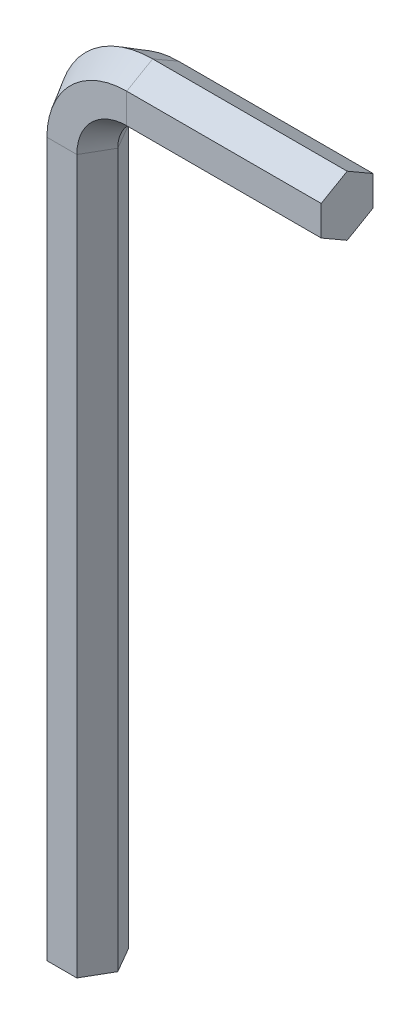
SolidWorks part; units mm, degrees
ref_plane "Front Plane" through (0, 0, 0) normal (0, 0, 1) x (1, 0, 0)
ref_plane "Top Plane" through (0, 0, 0) normal (0, 1, 0) x (1, 0, 0)
ref_plane "Right Plane" through (0, 0, 0) normal (1, 0, 0) x (0, 0, -1)
sketch "Sketch1" plane through (0, 0, 0) normal (0, 0, 1) x (1, 0, 0)
  line L0 (0, 0) -> (0, 110)
  line L1 (10, 120) -> (40, 120)
  arc A0 (0, 110) -> (10, 120) centre (10, 110) cw
  point P6 (0, 120)
  dimension "D3" = 10
  dimension "D1" = 120
  dimension "D2" = 40
sketch "Sketch2" plane through (0, 0, 0) normal (0, 1, 0) x (1, 0, 0)
  line L1 (4.6188, 0) -> (2.3094, 4)
  line L2 (2.3094, 4) -> (-2.3094, 4)
  line L3 (-2.3094, 4) -> (-4.6188, 0)
  line L4 (-4.6188, 0) -> (-2.3094, -4)
  line L5 (-2.3094, -4) -> (2.3094, -4)
  line L6 (2.3094, -4) -> (4.6188, 0)
  circle A0 centre (0, 0) radius 4 construction
  dimension "D1" = 8
  dimension "D2" = 4
sweep "Sweep1" add profiles "Sketch2" path "Sketch1"
